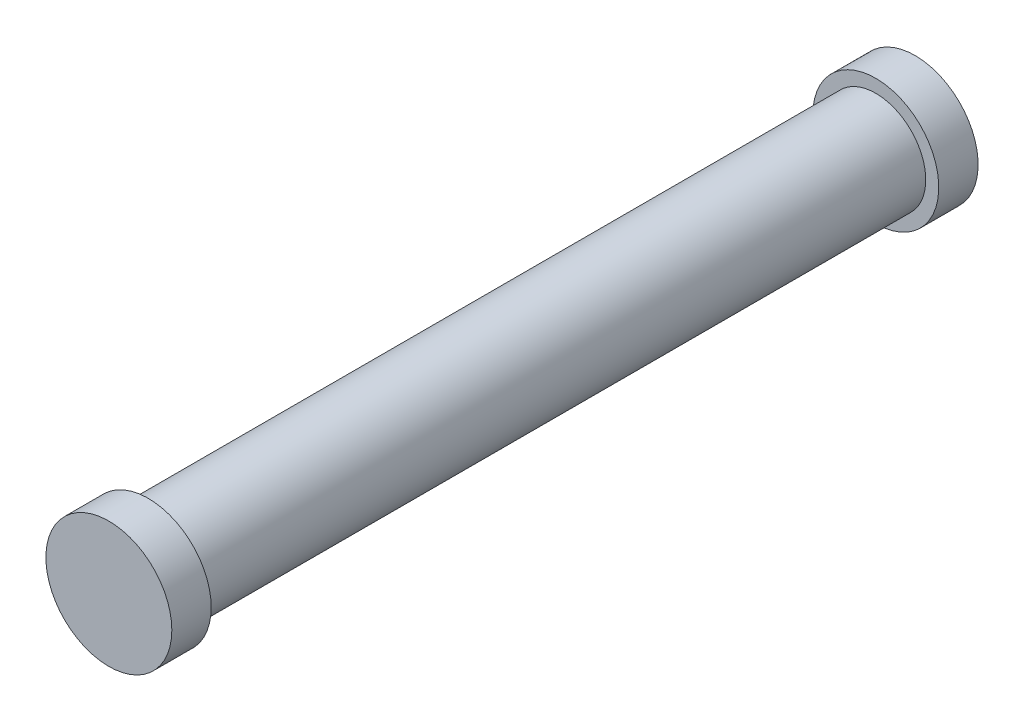
SolidWorks part; units mm, degrees
ref_plane "Front Plane" through (0, 0, 0) normal (0, 0, 1) x (1, 0, 0)
ref_plane "Top Plane" through (0, 0, 0) normal (0, 1, 0) x (1, 0, 0)
ref_plane "Right Plane" through (0, 0, 0) normal (1, 0, 0) x (0, 0, -1)
sketch "Sketch1" plane through (0, 0, 0) normal (0, 0, 1) x (1, 0, 0)
  circle A0 centre (0, 0) radius 9.525
extrude "Boss-Extrude1" add sketch "Sketch1" along normal blind 138.6311
sketch "Sketch2" plane through (0, 0, 138.6311) normal (0, 0, 1) x (1, 0, 0)
  circle A0 centre (0, 0) radius 12
extrude "Boss-Extrude2" add sketch "Sketch2" along normal blind 7.5
sketch "Sketch3" plane through (0, 0, 0) normal (0, 0, -1) x (-1, 0, 0)
  circle A0 centre (0, 0) radius 12
extrude "Boss-Extrude3" add sketch "Sketch3" along normal blind 7.5
